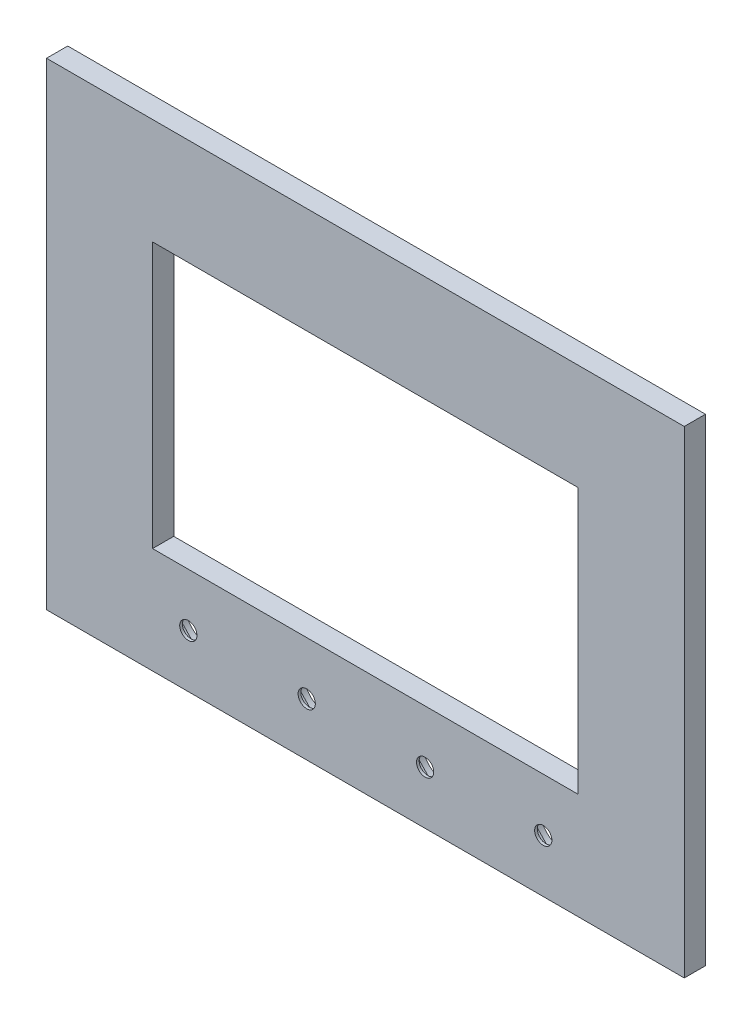
SolidWorks part; units mm, degrees
ref_plane "Front Plane" through (0, 0, 0) normal (0, 0, 1) x (1, 0, 0)
ref_plane "Top Plane" through (0, 0, 0) normal (0, 1, 0) x (1, 0, 0)
ref_plane "Right Plane" through (0, 0, 0) normal (1, 0, 0) x (0, 0, -1)
ref_plane "Plane1" through (0, 0, 0) normal (0, 0, -1) x (-1, 0, 0)
sketch "Sketch1" plane through (0, 0, 0) normal (0, 0, -1) x (-1, 0, 0)
  line L0 (69.5977, -77.75) -> (69.5977, 102.45)
  line L1 (69.5977, 102.45) -> (-171.0023, 102.45)
  line L2 (-171.0023, 102.45) -> (-171.0023, -77.75)
  line L3 (-171.0023, -77.75) -> (69.5977, -77.75)
extrude "Boss-Extrude1" add sketch "Sketch1" against normal blind 8
sketch "Sketch2" plane through (0, 0, 8) normal (0, 0, 1) x (1, 0, 0)
  line L0 (-29.5977, 62.45) -> (-29.5977, -37.75)
  line L1 (-29.5977, -37.75) -> (131.0023, -37.75)
  line L2 (131.0023, -37.75) -> (131.0023, 62.45)
  line L3 (131.0023, 62.45) -> (-29.5977, 62.45)
extrude "Cut-Extrude1" cut sketch "Sketch2" against normal through all
sketch "Sketch3" plane through (0, 0, 0) normal (0, 0, -1) x (-1, 0, 0)
  line L0 (-117.6868, -48.4833) -> (-127.0608, -58.1981)
  line L1 (-127.0608, -58.1981) -> (-117.9217, -67.0167)
  line L2 (-117.9217, -67.0167) -> (-108.5476, -57.3019)
  line L3 (-108.5476, -57.3019) -> (-117.6868, -48.4833)
extrude "Cut-Extrude2" cut sketch "Sketch3" against normal blind 7
sketch "Sketch4" plane through (0, 0, 0) normal (0, 0, -1) x (-1, 0, 0)
  line L0 (6.9392, -58.1981) -> (16.0783, -67.0167)
  line L1 (16.0783, -67.0167) -> (25.4524, -57.3019)
  line L2 (25.4524, -57.3019) -> (16.3132, -48.4833)
  line L3 (16.3132, -48.4833) -> (6.9392, -58.1981)
extrude "Cut-Extrude3" cut sketch "Sketch4" against normal blind 7
sketch "Sketch5" plane through (0, 0, 0) normal (0, 0, -1) x (-1, 0, 0)
  line L0 (-37.7275, -58.1981) -> (-28.5883, -67.0167)
  line L1 (-28.5883, -67.0167) -> (-19.2143, -57.3019)
  line L2 (-19.2143, -57.3019) -> (-28.3534, -48.4833)
  line L3 (-28.3534, -48.4833) -> (-37.7275, -58.1981)
extrude "Cut-Extrude4" cut sketch "Sketch5" against normal blind 7
sketch "Sketch6" plane through (0, 0, 0) normal (0, 0, -1) x (-1, 0, 0)
  line L0 (-82.3941, -58.1981) -> (-73.255, -67.0167)
  line L1 (-73.255, -67.0167) -> (-63.881, -57.3019)
  line L2 (-63.881, -57.3019) -> (-73.0201, -48.4833)
  line L3 (-73.0201, -48.4833) -> (-82.3941, -58.1981)
extrude "Cut-Extrude5" cut sketch "Sketch6" against normal blind 7
hole_wizard "Ø6.5 (6.5) Diameter Hole1" positions "Sketch8" profile "Sketch7" hole size "Ø6.5" standard "ANSI Metric"
sketch "Sketch8" plane through (0, 0, 8) normal (0, 0, 1) x (1, 0, 0)
  point P0 (117.8042, -57.75)
  point P1 (-16.0977, -57.75)
  point P2 (28.569, -57.75)
  point P3 (73.2357, -57.75)
sketch "Sketch7" plane through (117.8042, -57.75, 8) normal (1, 0, 0) x (0, -1, 0)
  line L0 (0, 0) -> (0, 8)
  line L1 (0, 8) -> (3.25, 8)
  line L2 (3.25, 8) -> (3.25, 0)
  line L5 (3.25, 0) -> (0, 0)
  line L11 (0, -6.35) -> (0, 107.95) construction
  dimension "Thru Hole Dia." = 6.5
  dimension "Thru Hole Depth" = 8
sketch "Sketch9" plane through (0, 0, 0) normal (0, 0, -1) x (-1, 0, 0)
  line L0 (-126.9808, -58.2753) -> (-117.9867, -66.9539)
  line L3 (-127.0608, -58.1981) -> (-117.9217, -67.0167) construction
  line L4 (-117.6868, -48.4833) -> (-108.5476, -57.3019)
  line L7 (-108.5476, -57.3019) -> (-117.6868, -48.4833) construction
  line L8 (-117.6868, -48.4833) -> (-127.0608, -58.1981) construction
  line L9 (-117.9217, -67.0167) -> (-108.5476, -57.3019) construction
  circle A0 centre (-117.8042, -57.75) radius 9.2674
  circle A1 centre (-73.2357, -57.75) radius 9.2692
  circle A2 centre (-28.569, -57.75) radius 9.2692
  circle A3 centre (16.0977, -57.75) radius 9.2667
  point P0 (-117.8042, -57.75)
  line M2 (-82.3941, -58.1981) -> (-73.0201, -48.4833)
  line M3 (-73.0201, -48.4833) -> (-63.881, -57.3019)
  line M4 (-63.881, -57.3019) -> (-73.255, -67.0167)
  line M5 (-73.255, -67.0167) -> (-82.3941, -58.1981)
  line M6 (-37.7275, -58.1981) -> (-28.3534, -48.4833)
  line M7 (-28.3534, -48.4833) -> (-19.2143, -57.3019)
  line M8 (-19.2143, -57.3019) -> (-28.5883, -67.0167)
  line M9 (-28.5883, -67.0167) -> (-37.7275, -58.1981)
  line M10 (6.9392, -58.1981) -> (16.3132, -48.4833)
  line M11 (16.3132, -48.4833) -> (25.4524, -57.3019)
  line M12 (25.4524, -57.3019) -> (16.0783, -67.0167)
  line M13 (16.0783, -67.0167) -> (6.9392, -58.1981)
  line M14 (-117.6868, -48.4833) -> (-108.5476, -57.3019)
  line M15 (-108.5476, -57.3019) -> (-117.9217, -67.0167)
  line M16 (-117.9217, -67.0167) -> (-127.0608, -58.1981)
  line M17 (-127.0608, -58.1981) -> (-117.6868, -48.4833)
extrude "Cut-Extrude7" cut sketch "Sketch9" against normal blind 4 contours A0 M14 | A0 M16 | A0 M17 | A0 M15 | A1 M2 M4 M5 | A1 M3 | A2 M6 M8 M9 | A2 M7 | A3 M10 M13 | A3 M12 | A3 M11
sketch "Sketch10" plane through (0, 0, 0) normal (0, 0, -1) x (-1, 0, 0)
  circle A0 centre (-127.0023, 69.25) radius 1.5
  circle A1 centre (29.9977, 69.25) radius 1.5
  circle A2 centre (29.9977, -45.75) radius 1.5
  circle A3 centre (-127.0023, -45.75) radius 1.5
extrude "Cut-Extrude8" cut sketch "Sketch10" against normal blind 0.5
